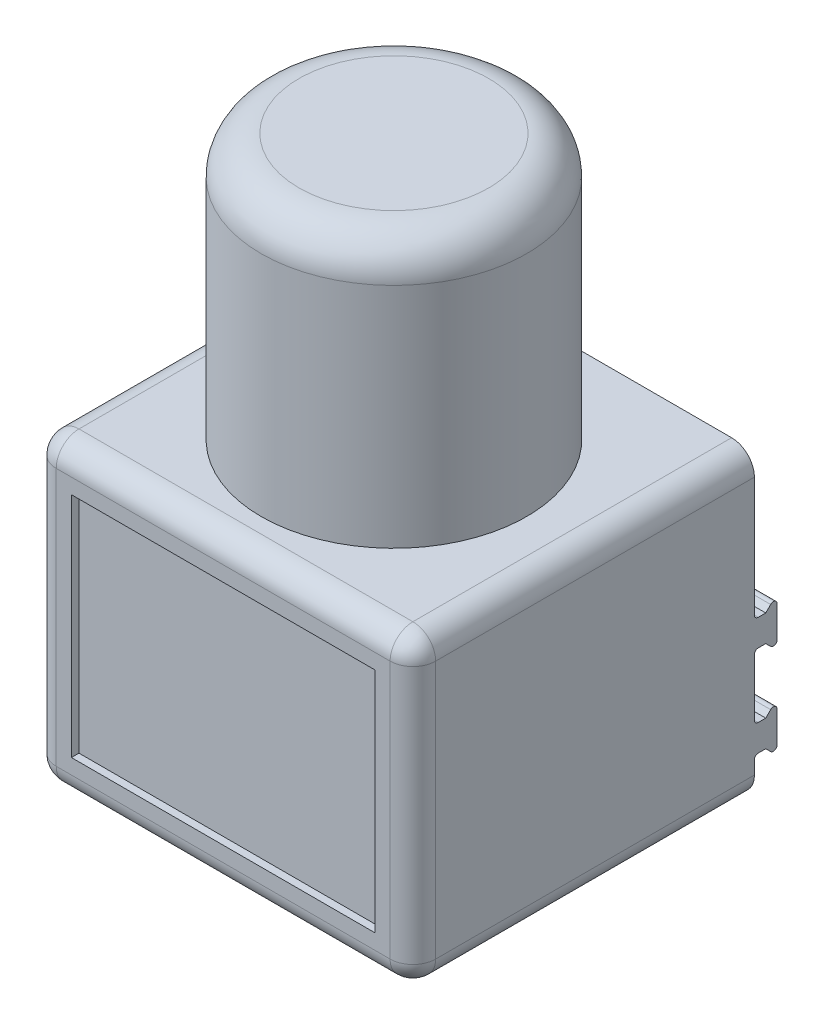
SolidWorks part; units mm, degrees
ref_plane "前视基准面" through (0, 0, 0) normal (0, 0, 1) x (1, 0, 0)
ref_plane "上视基准面" through (0, 0, 0) normal (0, 1, 0) x (1, 0, 0)
ref_plane "右视基准面" through (0, 0, 0) normal (1, 0, 0) x (0, 0, -1)
other "Configuration Table"
sketch "Sketch1" plane through (0, 0, 0) normal (0, 1, 0) x (1, 0, 0)
  line L1 (-250, -225) -> (250, -225)
  line L2 (-250, -225) -> (-250, 225)
  line L3 (-250, 225) -> (250, 225)
  line L4 (250, -225) -> (250, 225)
  line L5 (-250, -225) -> (250, 225) construction
  line L6 (-250, 225) -> (250, -225) construction
  point P0 (0, 0)
  dimension "D1" = 450
  dimension "D2" = 500
extrude "Boss-Extrude1" add sketch "Sketch1" along normal mid plane 400
sketch "Sketch2" plane through (250, 0, 0) normal (1, 0, 0) x (0, 0, -1)
  line L0 (225, -10) -> (205, -10) construction
  line L1 (225, 200) -> (225, -200) construction
  line L2 (-225, -200) -> (225, -200) construction
  line L3 (225, -130) -> (255, -130) construction
  line L13 (240, -27.5) -> (255, -42.5)
  line L14 (255, -42.5) -> (255, 22.5)
  line L15 (255, 22.5) -> (240, 7.5)
  line L16 (240, 7.5) -> (225, 7.5)
  line L17 (225, 7.5) -> (225, -27.5)
  line L18 (225, -27.5) -> (240, -27.5)
  line L19 (225, -147.5) -> (225, -112.5)
  line L20 (225, -112.5) -> (240, -112.5)
  line L21 (240, -147.5) -> (225, -147.5)
  line L22 (255, -162.5) -> (240, -147.5)
  line L23 (255, -97.5) -> (255, -162.5)
  line L24 (240, -112.5) -> (255, -97.5)
  dimension "D1" = 120
  dimension "D3" = 35
  dimension "D4" = 30
  dimension "D5" = 15
  dimension "D2" = 45
  dimension "D6" = 45
  dimension "D7" = 70
extrude "Boss-Extrude2" add sketch "Sketch2" against normal up to surface (500 mm away) up to face at (-250, 0, 0)
fillet "Fillet1" radius 5 8 edges at (0, -162.5, -255) (0, -147.5, -225) (0, -97.5, -255) (0, -112.5, -225) (0, -27.5, -225) (0, -42.5, -255) (0, 22.5, -255) (0, 7.5, -225)
sketch "Sketch3" plane through (0, -200, 0) normal (0, -1, 0) x (1, 0, 0)
  circle A0 centre (0, 0) radius 150
  dimension "D1" = 300
extrude "Cut-Extrude1" cut sketch "Sketch3" against normal blind 200
sketch "Sketch4" plane through (0, 200, 0) normal (0, 1, 0) x (1, 0, 0)
  circle A0 centre (0, 0) radius 175
  dimension "D1" = 350
extrude "Boss-Extrude3" add sketch "Sketch4" along normal blind 350
fillet "Fillet2" radius 50 1 edges at (0, 550, 175)
fillet "Fillet3" radius 30 8 edges at (-250, 0, 225) (-250, -200, 0) (0, -200, 225) (250, -200, 0) (250, 0, 225) (250, 200, 0) (0, 200, 225) (-250, 200, 0)
sketch "Sketch5" plane through (0, 0, 225) normal (0, 0, 1) x (1, 0, 0)
  line L18 (-200, -150) -> (200, -150)
  line L19 (200, -150) -> (200, 150)
  line L20 (-200, 150) -> (-200, -150)
  line L21 (200, 150) -> (-200, 150)
  line L22 (-200, -150) -> (200, -150)
  line L23 (200, -150) -> (200, 150)
  line L24 (-200, 150) -> (-200, -150)
  line L25 (200, 150) -> (-200, 150)
  dimension "D1" = 20
extrude "Cut-Extrude2" cut sketch "Sketch5" against normal blind 10
ref_plane "Plane1" through (0, -470, 0) normal (0, -1, 0) x (-1, 0, 0)
sketch "Sketch7" plane through (0, -470, 0) normal (0, -1, 0) x (-1, 0, 0)
  point P0 (0, 0)
